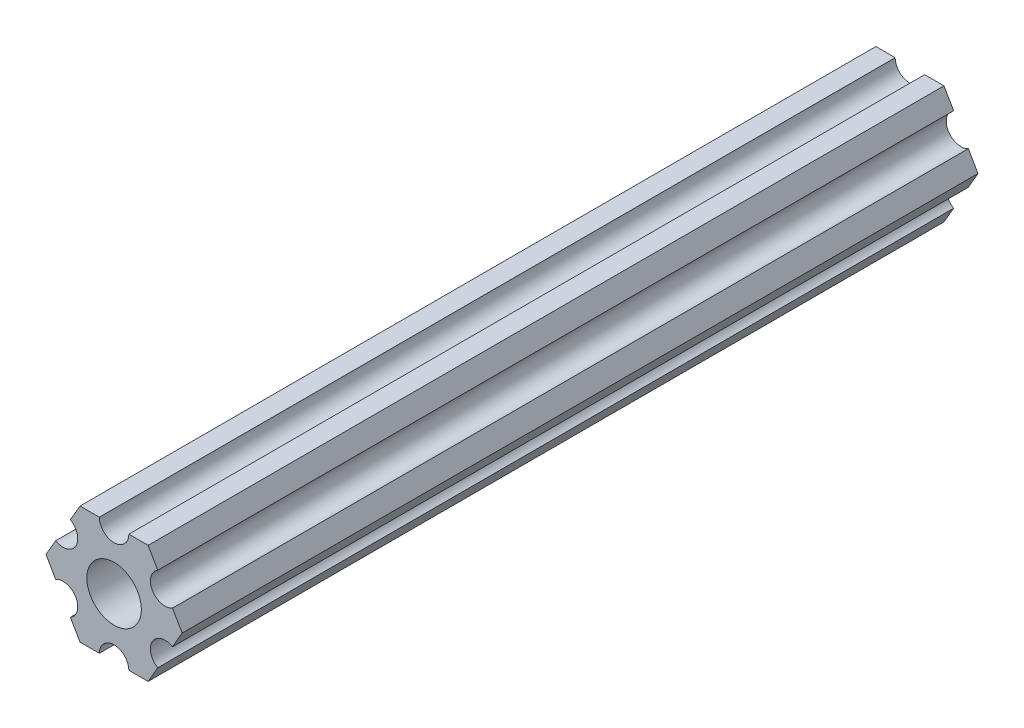
SolidWorks part; units mm, degrees
material "6061 Alloy"
ref_plane "Front Plane" through (0, 0, 0) normal (0, 0, 1) x (1, 0, 0)
ref_plane "Top Plane" through (0, 0, 0) normal (0, 1, 0) x (1, 0, 0)
ref_plane "Right Plane" through (0, 0, 0) normal (1, 0, 0) x (0, 0, -1)
sketch "Sketch1" plane through (0, 0, 0) normal (0, 0, 1) x (1, 0, 0)
  line L0 (3.6662, -6.35) -> (4.7055, -4.5498)
  line L1 (6.293, -1.8002) -> (7.3323, 0)
  line L2 (7.3323, 0) -> (6.293, 1.8002)
  line L3 (4.7055, 4.5498) -> (3.6662, 6.35)
  line L4 (3.6662, 6.35) -> (1.5875, 6.35)
  line L5 (-1.5875, 6.35) -> (-3.6662, 6.35)
  line L6 (-3.6662, 6.35) -> (-4.7055, 4.5498)
  line L7 (-6.293, 1.8002) -> (-7.3323, 0)
  line L8 (-7.3323, 0) -> (-6.293, -1.8002)
  line L9 (-4.7055, -4.5498) -> (-3.6662, -6.35)
  line L10 (-3.6662, -6.35) -> (-1.5875, -6.35)
  line L11 (1.5875, -6.35) -> (3.6662, -6.35)
  circle A0 centre (0, 0) radius 2.9337
  arc A1 (4.7055, -4.5498) -> (6.293, -1.8002) centre (5.4993, -3.175) cw
  arc A2 (6.293, 1.8002) -> (4.7055, 4.5498) centre (5.4993, 3.175) cw
  arc A3 (1.5875, 6.35) -> (-1.5875, 6.35) centre (0, 6.35) cw
  arc A4 (-4.7055, 4.5498) -> (-6.293, 1.8002) centre (-5.4993, 3.175) cw
  arc A5 (-6.293, -1.8002) -> (-4.7055, -4.5498) centre (-5.4993, -3.175) cw
  arc A6 (-1.5875, -6.35) -> (1.5875, -6.35) centre (0, -6.35) cw
  dimension "D1" = 5.8674
  dimension "D2" = 1.5875
  dimension "D3" = 3.6662
  dimension "D4" = 5.4993
extrude "Boss-Extrude1" add sketch "Sketch1" against normal blind 85.725
